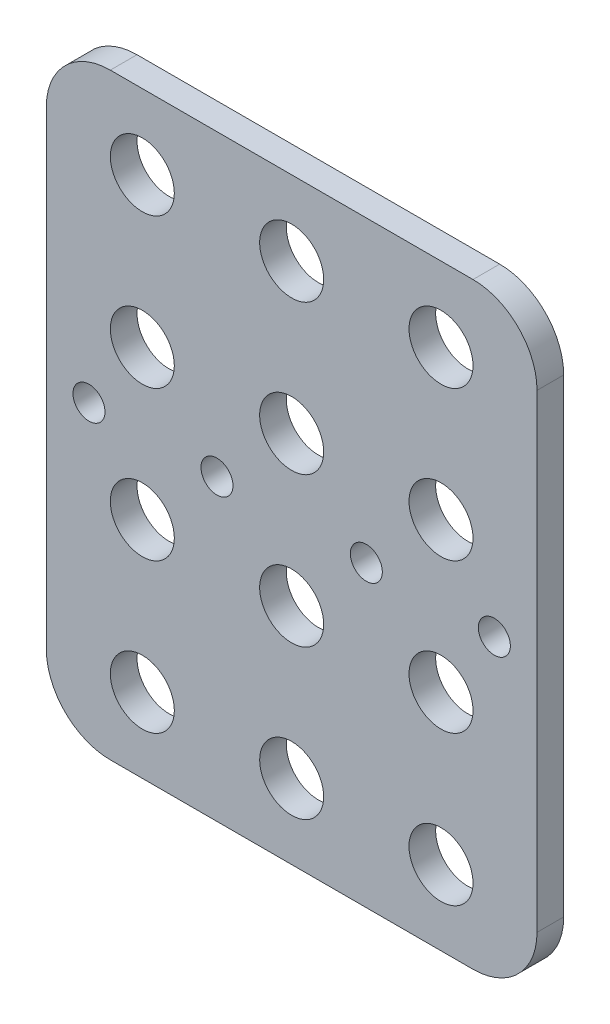
SolidWorks part; units mm, degrees
ref_plane "前视基准面" through (0, 0, 0) normal (0, 0, 1) x (1, 0, 0)
ref_plane "上视基准面" through (0, 0, 0) normal (0, 1, 0) x (1, 0, 0)
ref_plane "右视基准面" through (0, 0, 0) normal (1, 0, 0) x (0, 0, -1)
sketch "草图1" plane through (0, 0, 0) normal (0, 0, 1) x (1, 0, 0)
  line L1 (-23, 28) -> (23, 28)
  line L2 (-23, 28) -> (-23, -28)
  line L3 (-23, -28) -> (23, -28)
  line L4 (23, 28) -> (23, -28)
  line L5 (0, -28) -> (0, 28) construction
  line L6 (-23, 0) -> (23, 0) construction
  point P0 (0, 0)
  dimension "D1" = 56
  dimension "D2" = 46
extrude "凸台-拉伸1" add sketch "草图1" along normal blind 2.5
fillet "圆角1" radius 6 4 edges at (23, 28, 1.25) (23, -28, 1.25) (-23, -28, 1.25) (-23, 28, 1.25)
sketch "草图2" plane through (0, 0, 2.5) normal (0, 0, 1) x (1, 0, 0)
  line L0 (0, 0) -> (0, 7) construction
  circle A0 centre (-19, 0) radius 1.5
  circle A1 centre (-7, 0) radius 1.5
  circle A2 centre (7, 0) radius 1.5
  circle A3 centre (19, 0) radius 1.5
  dimension "D1" = 3
  dimension "D2" = 3
extrude "切除-拉伸1" cut sketch "草图2" against normal blind 10
sketch "草图3" plane through (0, 0, 2.5) normal (0, 0, 1) x (1, 0, 0)
  line L0 (0, 0) -> (25.6318, 0) construction
  circle A0 centre (-14, 7) radius 3
  circle A1 centre (0, 7) radius 3
  circle A2 centre (14, 7) radius 3
  circle A3 centre (-14, -7) radius 3
  circle A4 centre (0, -7) radius 3
  circle A5 centre (14, -7) radius 3
  circle A6 centre (-14, 21) radius 3
  circle A7 centre (0, 21) radius 3
  circle A8 centre (14, 21) radius 3
  circle A9 centre (14, -21) radius 3
  circle A10 centre (0, -21) radius 3
  circle A11 centre (-14, -21) radius 3
  dimension "D1" = 6
  dimension "D4" = 6
  dimension "D6" = 6
  dimension "D7" = 6
  dimension "D5" = 14
  dimension "D2" = 3
  dimension "D3" = 2
extrude "切除-拉伸2" cut sketch "草图3" against normal blind 10
